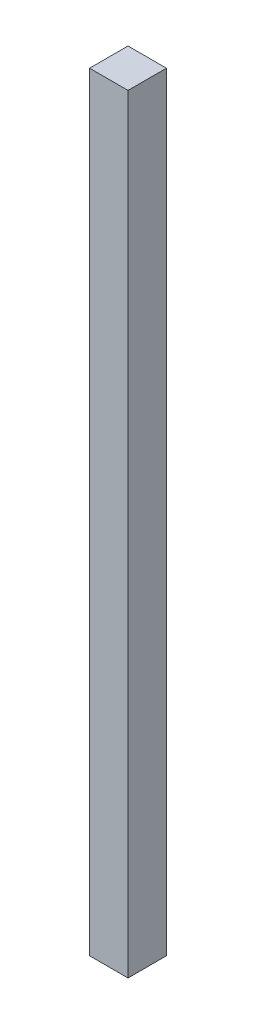
SolidWorks part; units mm, degrees
material "6061-T6 (SS)"
ref_plane "Front Plane" through (0, 0, 0) normal (0, 0, 1) x (1, 0, 0)
ref_plane "Top Plane" through (0, 0, 0) normal (0, 1, 0) x (1, 0, 0)
ref_plane "Right Plane" through (0, 0, 0) normal (1, 0, 0) x (0, 0, -1)
sketch "Sketch1" plane through (0, 0, 0) normal (0, 1, 0) x (1, 0, 0)
  line L1 (-2.5, -2.5) -> (2.5, -2.5)
  line L2 (-2.5, -2.5) -> (-2.5, 2.5)
  line L3 (-2.5, 2.5) -> (2.5, 2.5)
  line L4 (2.5, -2.5) -> (2.5, 2.5)
  line L5 (-2.5, -2.5) -> (2.5, 2.5) construction
  line L6 (-2.5, 2.5) -> (2.5, -2.5) construction
  point P0 (0, 0)
  dimension "D1" = 5
extrude "Boss-Extrude1" add sketch "Sketch1" along normal blind 100
